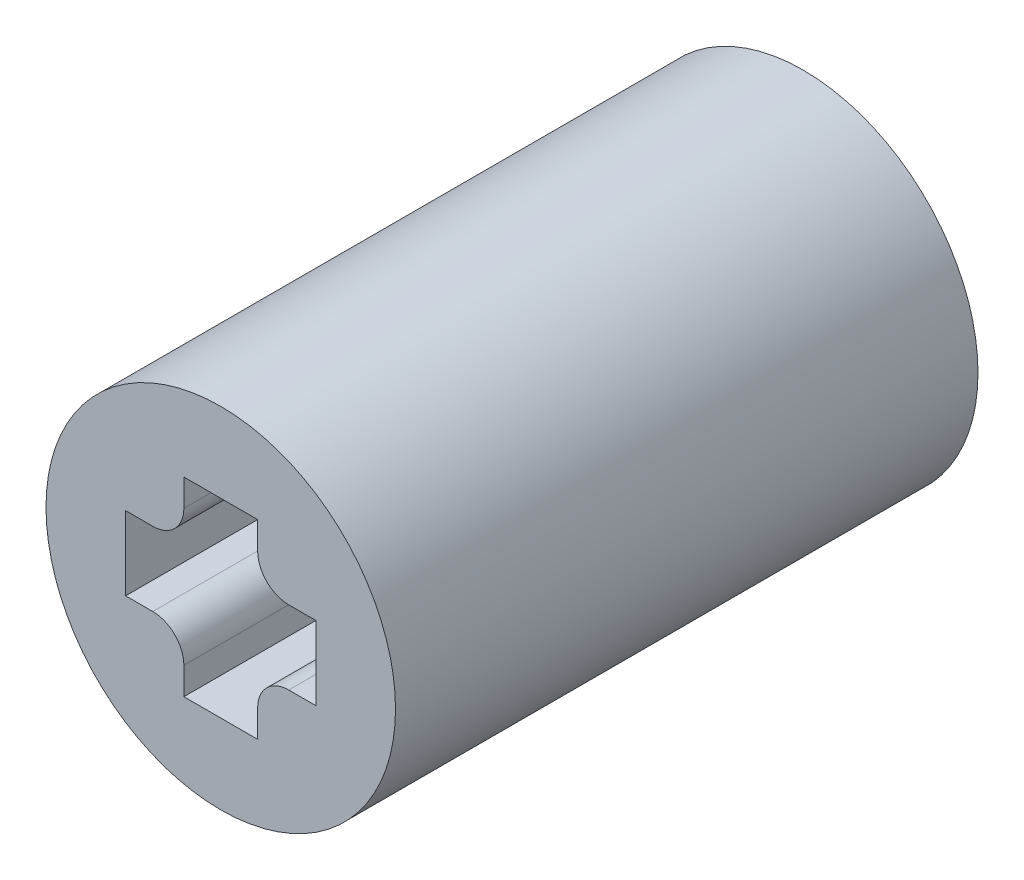
SolidWorks part; units mm, degrees
ref_plane "Front Plane" through (0, 0, 0) normal (0, 0, 1) x (1, 0, 0)
ref_plane "Top Plane" through (0, 0, 0) normal (0, 1, 0) x (1, 0, 0)
ref_plane "Right Plane" through (0, 0, 0) normal (1, 0, 0) x (0, 0, -1)
sketch "Sketch1" plane through (0, 0, 0) normal (0, 0, 1) x (1, 0, 0)
  circle A0 centre (0, 0) radius 4.5
  dimension "D1" = 9
extrude "Boss-Extrude1" add sketch "Sketch1" along normal blind 15
sketch "Sketch2" plane through (0, 0, 0) normal (0, 0, -1) x (-1, 0, 0)
  line L1 (-2, 3) -> (2, 3)
  line L2 (-2, 3) -> (-2, -3)
  line L3 (-2, -3) -> (2, -3)
  line L4 (2, 3) -> (2, -3)
  line L5 (-2, 3) -> (2, -3) construction
  line L6 (-2, -3) -> (2, 3) construction
  point P0 (0, 0)
  dimension "D1" = 4
  dimension "D2" = 6
extrude "Cut-Extrude1" cut sketch "Sketch2" against normal blind 7
sketch "Sketch3" plane through (0, 0, 15) normal (0, 0, 1) x (1, 0, 0)
  line L0 (-0.95, -0.95) -> (-0.95, -2.45)
  line L1 (-2.45, 0.95) -> (-0.95, 0.95)
  line L2 (-2.45, 0.95) -> (-2.45, -0.95)
  line L3 (-2.45, -0.95) -> (-0.95, -0.95)
  line L4 (2.45, 0.95) -> (2.45, -0.95)
  line L7 (-0.95, 2.45) -> (0.95, 2.45)
  line L8 (-0.95, 2.45) -> (-0.95, 0.95)
  line L9 (-0.95, -2.45) -> (0.95, -2.45)
  line L10 (0.95, 2.45) -> (0.95, 0.95)
  line L15 (0.95, 0.95) -> (2.45, 0.95)
  line L17 (0.95, -0.95) -> (0.95, -2.45)
  line L19 (0.95, -0.95) -> (2.45, -0.95)
  point P0 (0, 0)
  point P5 (0, 0)
  dimension "D1" = 4.9
  dimension "D2" = 1.9
  dimension "D3" = 4.9
  dimension "D4" = 1.9
extrude "Cut-Extrude2" cut sketch "Sketch3" against normal blind 7
fillet "Fillet3" radius 0.8 4 edges at (-0.95, -0.95, 11.5) (0.95, -0.95, 11.5) (-0.95, 0.95, 11.5) (0.95, 0.95, 11.5)
